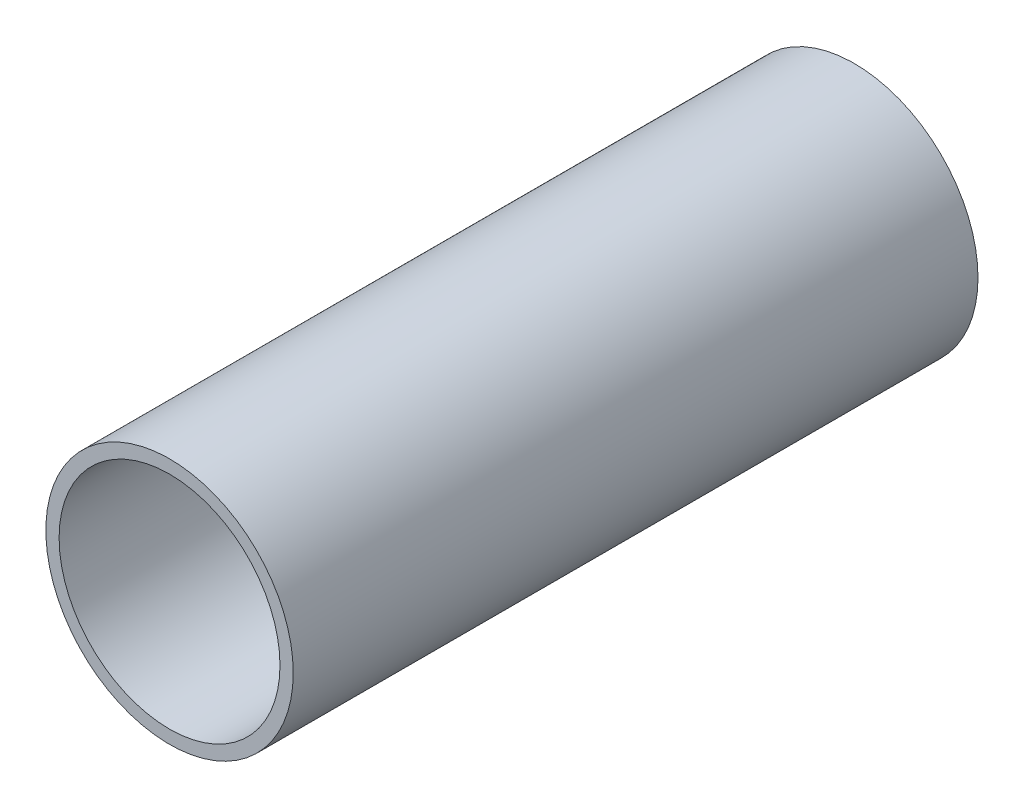
SolidWorks part; units mm, degrees
ref_plane "Front Plane" through (0, 0, 0) normal (0, 0, 1) x (1, 0, 0)
ref_plane "Top Plane" through (0, 0, 0) normal (0, 1, 0) x (1, 0, 0)
ref_plane "Right Plane" through (0, 0, 0) normal (1, 0, 0) x (0, 0, -1)
sketch "Sketch1" plane through (0, 0, 0) normal (0, 0, 1) x (1, 0, 0)
  circle A0 centre (0, 0) radius 56
  dimension "D1" = 112
extrude "Boss-Extrude1" add sketch "Sketch1" along normal blind 310
sketch "Sketch2" plane through (0, 0, 310) normal (0, 0, 1) x (1, 0, 0)
  circle A0 centre (0, 0) radius 50
  dimension "D1" = 100
extrude "Cut-Extrude1" cut sketch "Sketch2" against normal blind 310
